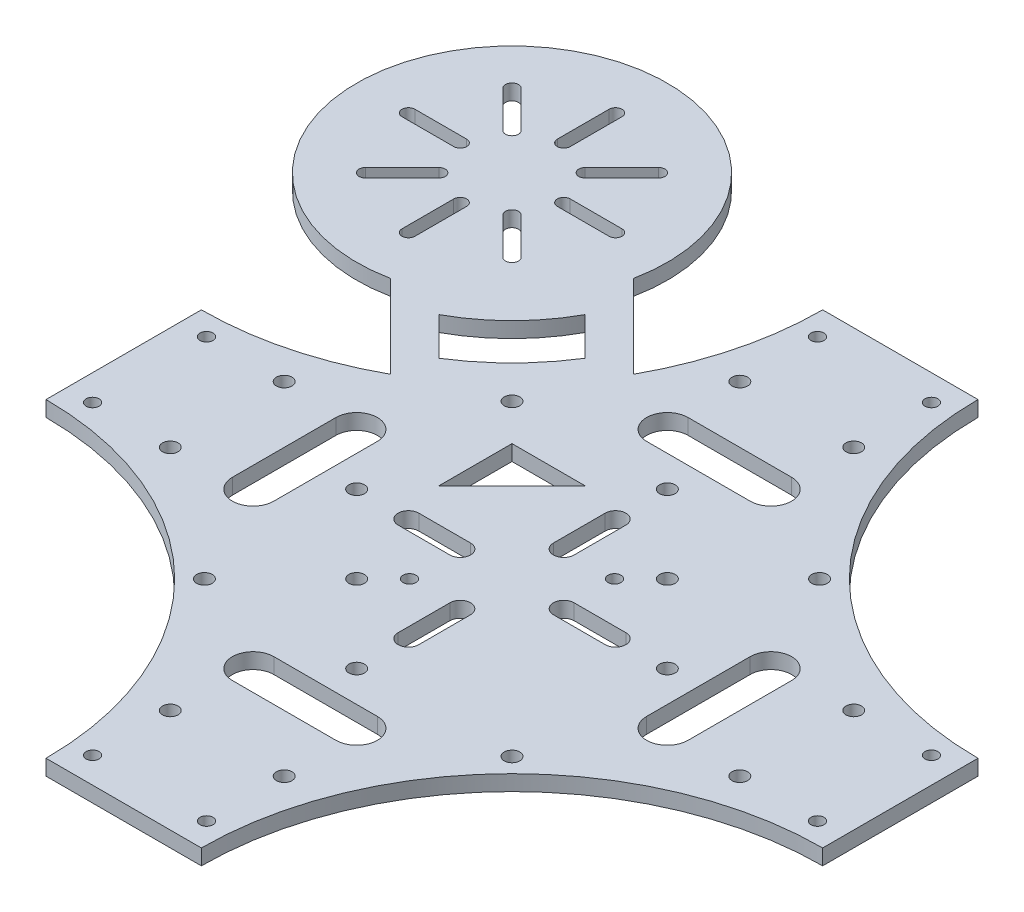
SolidWorks part; units mm, degrees
ref_plane "前视基准面" through (0, 0, 0) normal (0, 0, 1) x (1, 0, 0)
ref_plane "上视基准面" through (0, 0, 0) normal (0, 1, 0) x (1, 0, 0)
ref_plane "右视基准面" through (0, 0, 0) normal (1, 0, 0) x (0, 0, -1)
sketch "草图1" plane through (0, 0, 0) normal (0, 1, 0) x (1, 0, 0)
  line L0 (0, 0) -> (0, 75)
  line L1 (0, 0) -> (75, 0)
  line L2 (0, 0) -> (0, -75)
  line L3 (0, 0) -> (-75, 0)
  line L4 (0, 75) -> (15, 75)
  line L5 (0, 75) -> (-15, 75)
  line L6 (75, 0) -> (75, 15)
  line L7 (75, 0) -> (75, -15)
  line L8 (0, -75) -> (15, -75)
  line L9 (0, -75) -> (-15, -75)
  line L10 (-75, 0) -> (-75, -15)
  line L11 (-75, 0) -> (-75, 15)
  line L12 (75, 0) -> (70, 0)
  arc A0 (-75, 15) -> (-15, 75) centre (-75, 75) ccw
  arc A1 (15, 75) -> (75, 15) centre (75, 75) ccw
  arc A2 (75, -15) -> (15, -75) centre (75, -75) ccw
  arc A3 (-15, -75) -> (-75, -15) centre (-75, -75) ccw
  circle A4 centre (-11, 70) radius 1.25
  circle A5 centre (11, 70) radius 1.25
  circle A6 centre (70, -11) radius 1.25
  circle A7 centre (70, 11) radius 1.25
  circle A8 centre (-11, -70) radius 1.25
  circle A9 centre (11, -70) radius 1.25
  circle A10 centre (-70, 11) radius 1.25
  circle A11 centre (-70, -11) radius 1.25
  point P9 (0, 0)
  point P21 (0, 0)
  point P32 (0, 0)
  point P35 (0, 0)
  point P44 (0, 0)
  dimension "D1" = 4
extrude "凸台-拉伸1" add sketch "草图1" along normal blind 3 contours A2 L7 L1 L2 L8 A9 A6 | A3 L9 L2 L3 L10 A11 A8 | A0 L11 L3 L0 L5 A4 A10 | A1 L4 L0 L1 L6 A7 A5
sketch "草图2" plane through (0, 0, 0) normal (0, -1, 0) x (1, 0, 0)
  line L0 (0, 0) -> (-32.5736, -32.5736)
  line L1 (0, 0) -> (32.5736, -32.5736)
  line L2 (-31.4663, 0.3536) -> (-0.3536, 31.4663)
  line L3 (31.4663, -0.3536) -> (-0.3536, 31.4663)
  line L4 (0.3536, -31.4663) -> (31.4663, -0.3536)
  line L5 (0.3536, -31.4663) -> (-31.4663, 0.3536)
  arc A0 (-15, -75) -> (-75, -15) centre (-75, -75) ccw construction
  circle A2 centre (0.3536, -31.4663) radius 1.5
  circle A3 centre (31.4663, -0.3536) radius 1.5
  circle A4 centre (-0.3536, 31.4663) radius 1.5
  circle A5 centre (-31.4663, 0.3536) radius 1.5
  point P12 (-15.5563, -15.5563)
  point P16 (-15.9099, 15.9099)
  point P17 (15.9099, -15.9099)
extrude "切除-拉伸1" cut sketch "草图2" against normal blind 3 contours A3 | A2 | A5 | A4
sketch "草图3" plane through (0, 3, 0) normal (0, 1, 0) x (1, 0, 0)
  line L0 (0.3536, 31.4663) -> (-31.4663, -0.3536)
  line L1 (-15.5563, 15.5563) -> (-22.6274, 22.6274)
  line L2 (-15.5563, 15.5563) -> (-12.0208, 19.0919)
  line L3 (-15.5563, 15.5563) -> (-19.0919, 12.0208)
  line L4 (-19.0919, 12.0208) -> (-22.6274, 22.6274)
  line L5 (-12.0208, 19.0919) -> (-22.6274, 22.6274)
extrude "切除-拉伸2" cut sketch "草图3" against normal blind 3 contours L0 L5 L1 | L4 L0 L1
sketch "草图4" plane through (0, 3, 0) normal (0, 1, 0) x (1, 0, 0)
  line L0 (31.4663, 0.3536) -> (-0.3536, -31.4663)
  line L1 (0, 0) -> (21.2132, -21.2132)
  line L2 (28.2843, -14.1421) -> (14.1421, -28.2843)
  line L3 (14.1421, -28.2843) -> (28.2843, -14.1421) construction
  line L4 (8.4817, -22.6239) -> (22.6239, -8.4817)
  line L5 (19.8025, -33.9447) -> (33.9447, -19.8025)
  arc A0 (8.4817, -22.6239) -> (19.8025, -33.9447) centre (14.1421, -28.2843) ccw
  arc A1 (33.9447, -19.8025) -> (22.6239, -8.4817) centre (28.2843, -14.1421) ccw
  point P9 (21.2132, -21.2132)
extrude "切除-拉伸3" cut sketch "草图4" against normal blind 3
sketch "草图5" plane through (0, 3, 0) normal (0, 1, 0) x (1, 0, 0)
  line L0 (-12.0208, 19.0919) -> (-8.4853, 22.6274)
  line L1 (-8.4853, 22.6274) -> (-22.6274, 22.6274)
  line L2 (-19.0919, 12.0208) -> (-22.6274, 8.4853)
  line L3 (-22.6274, 8.4853) -> (-22.6274, 22.6274)
  line L4 (-12.0208, 19.0919) -> (-22.6274, 22.6274)
  line M28 (-19.0919, 12.0208) -> (-22.6274, 22.6274)
extrude "切除-拉伸4" cut sketch "草图5" against normal blind 10 contours L3 L2 M28 | L4 L0 L1
sketch "草图6" plane through (0, 3, 0) normal (0, 1, 0) x (1, 0, 0)
  line L0 (0, 0) -> (-28.2843, -28.2843)
  line L1 (-28.2843, -28.2843) -> (-35.3553, -21.2132)
  line L2 (0, 0) -> (-22.6274, 22.6274)
  circle A0 centre (-35.3553, -21.2132) radius 1.5
  circle A1 centre (-21.2132, -35.3553) radius 1.5
  circle A2 centre (35.3553, 21.2132) radius 1.5
  circle A3 centre (21.2132, 35.3553) radius 1.5
extrude "切除-拉伸5" cut sketch "草图6" against normal blind 10 contours A1 | A0 | A2 | A3
sketch "草图7" plane through (0, 3, 0) normal (0, 1, 0) x (1, 0, 0)
  circle A0 centre (-29.6985, 29.6985) radius 1.5
  circle A1 centre (29.6985, 29.6985) radius 1.5
  circle A2 centre (29.6985, -29.6985) radius 1.5
  circle A3 centre (-29.6985, -29.6985) radius 1.5
  point P11 (0, 0)
  dimension "D1" = 4
extrude "切除-拉伸8" cut sketch "草图7" against normal blind 10
sketch "草图8" plane through (0, 3, 0) normal (0, 1, 0) x (1, 0, 0)
  circle A0 centre (-11, 55) radius 1.5
  circle A1 centre (11, 55) radius 1.5
  circle A2 centre (55, 11) radius 1.5
  circle A3 centre (55, -11) radius 1.5
  circle A4 centre (11, -55) radius 1.5
  circle A5 centre (-11, -55) radius 1.5
  circle A6 centre (-55, -11) radius 1.5
  circle A7 centre (-55, 11) radius 1.5
  point P21 (0, 0)
  dimension "D1" = 4
extrude "切除-拉伸9" cut sketch "草图8" against normal blind 10
sketch "草图9" plane through (0, 3, 0) normal (0, 1, 0) x (1, 0, 0)
  circle A0 centre (0, 0) radius 15
extrude "切除-拉伸10" cut sketch "草图9" against normal blind 10
sketch "草图11" plane through (0, 3, 0) normal (0, 1, 0) x (1, 0, 0)
  circle A0 centre (-35.3553, -21.2132) radius 1.5
  circle A2 centre (35.3553, 21.2132) radius 1.5
  circle A3 centre (21.2132, 35.3553) radius 1.5
  circle A4 centre (0.3536, 31.4663) radius 1.5
  circle A5 centre (31.4663, 0.3536) radius 1.5
  circle A6 centre (-0.3536, -31.4663) radius 1.5
  circle A7 centre (-31.4663, -0.3536) radius 1.5
  circle A8 centre (-21.2132, -35.3553) radius 1.5
extrude "凸台-拉伸3" add sketch "草图11" against normal blind 3
sketch "草图12" plane through (0, 3, 0) normal (0, 1, 0) x (1, 0, 0)
  line L0 (0, 0) -> (-40, 0)
  line L1 (-40, 0) -> (-40, 10)
  line L2 (-40, 0) -> (-40, -10)
  line L3 (-40, -10) -> (-40, 10) construction
  line L4 (-44, -10) -> (-44, 10)
  line L5 (-36, -10) -> (-36, 10)
  line L6 (-10, 40) -> (10, 40) construction
  line L7 (-10, 44) -> (10, 44)
  line L8 (-10, 36) -> (10, 36)
  line L9 (40, 10) -> (40, -10) construction
  line L10 (44, 10) -> (44, -10)
  line L11 (36, 10) -> (36, -10)
  line L12 (10, -40) -> (-10, -40) construction
  line L13 (10, -44) -> (-10, -44)
  line L14 (10, -36) -> (-10, -36)
  arc A0 (-44, -10) -> (-36, -10) centre (-40, -10) ccw
  arc A1 (-36, 10) -> (-44, 10) centre (-40, 10) ccw
  arc A2 (-10, 44) -> (-10, 36) centre (-10, 40) ccw
  arc A3 (10, 36) -> (10, 44) centre (10, 40) ccw
  arc A4 (44, 10) -> (36, 10) centre (40, 10) ccw
  arc A5 (36, -10) -> (44, -10) centre (40, -10) ccw
  arc A6 (10, -44) -> (10, -36) centre (10, -40) ccw
  arc A7 (-10, -36) -> (-10, -44) centre (-10, -40) ccw
  point P3 (-40, 0)
  point P13 (0, 40)
  point P20 (40, 0)
  point P27 (0, -40)
  point P34 (0, 0)
  dimension "D1" = 4
extrude "切除-拉伸12" cut sketch "草图12" against normal blind 3
sketch "草图14" plane through (0, 3, 0) normal (0, 1, 0) x (1, 0, 0)
  line L0 (22.8277, -8.285) -> (8.285, -22.8277) construction
  line L1 (19.8025, -33.9447) -> (33.9447, -19.8025) construction
  line L2 (8.285, -22.8277) -> (22.8277, -8.285)
  line L3 (22.8277, -8.285) -> (19.8025, -33.9447)
  line L4 (19.8025, -33.9447) -> (33.9447, -19.8025)
  arc A0 (8.285, -22.8277) -> (19.8025, -33.9447) centre (14.1421, -28.2843) ccw
  arc A1 (8.285, -22.8277) -> (19.8025, -33.9447) centre (14.1421, -28.2843) ccw construction
  arc A2 (33.9447, -19.8025) -> (22.8277, -8.285) centre (28.2843, -14.1421) ccw construction
  arc A3 (22.8277, -8.285) -> (32.1857, -7.1522) centre (28.2843, -14.1421) ccw
  circle A4 centre (28.2843, -14.1421) radius 8.005
extrude "凸台-拉伸4" add sketch "草图14" against normal blind 3 contours A3 A4 L3 | L2 A3 L3 | A3 L2 A0 L3 | A3 L3 L4
sketch "草图15" plane through (0, 3, 0) normal (0, 1, 0) x (1, 0, 0)
  circle A0 centre (0, 0) radius 15
extrude "凸台-拉伸5" add sketch "草图15" against normal blind 3
sketch "草图17" plane through (0, 3, 0) normal (0, 1, 0) x (1, 0, 0)
  line L0 (0, 0) -> (0, -20)
  line L1 (0, -20) -> (0, -10) construction
  line L2 (-2, -20) -> (-2, -10)
  line L3 (2, -20) -> (2, -10)
  line L4 (-20, 0) -> (-10, 0) construction
  line L5 (-20, 2) -> (-10, 2)
  line L6 (-20, -2) -> (-10, -2)
  line L7 (0, 20) -> (0, 10) construction
  line L8 (2, 20) -> (2, 10)
  line L9 (-2, 20) -> (-2, 10)
  line L10 (20, 0) -> (10, 0) construction
  line L11 (20, -2) -> (10, -2)
  line L12 (20, 2) -> (10, 2)
  arc A0 (-2, -20) -> (2, -20) centre (0, -20) ccw
  arc A1 (2, -10) -> (-2, -10) centre (0, -10) ccw
  arc A2 (-20, 2) -> (-20, -2) centre (-20, 0) ccw
  arc A3 (-10, -2) -> (-10, 2) centre (-10, 0) ccw
  arc A4 (2, 20) -> (-2, 20) centre (0, 20) ccw
  arc A5 (-2, 10) -> (2, 10) centre (0, 10) ccw
  arc A6 (20, -2) -> (20, 2) centre (20, 0) ccw
  arc A7 (10, 2) -> (10, -2) centre (10, 0) ccw
  point P3 (0, -15)
  point P13 (-15, 0)
  point P20 (0, 15)
  point P27 (15, 0)
  point P33 (0, 0)
  dimension "D1" = 4
extrude "切除-拉伸13" cut sketch "草图17" against normal blind 3 contours L8 A5 L9 A4 | L12 A7 L11 A6 | L3 A1 L2 A0 | L5 A3 L6 A2
sketch "草图18" plane through (0, 3, 0) normal (0, 1, 0) x (1, 0, 0)
  line L0 (0, 0) -> (-32.5736, 32.5736)
  line L1 (-32.5736, 32.5736) -> (-46.7157, 46.7157)
  line L2 (-50.2513, 50.2513) -> (-61.9773, 38.5252)
  line L3 (-46.7157, 46.7157) -> (-50.2513, 50.2513)
  line L4 (-61.9773, 38.5252) -> (-38.5252, 61.9773)
  line L5 (-38.5252, 61.9773) -> (-22.5002, 45.9523)
  line L6 (-61.9773, 38.5252) -> (-45.9523, 22.5002)
  arc A0 (-75, 15) -> (-15, 75) centre (-75, 75) ccw construction
  circle A1 centre (-67.9289, 67.9289) radius 30
  circle A2 centre (-75, 75) radius 60
extrude "凸台-拉伸7" add sketch "草图18" against normal blind 3 contours L4 A1 L2 | L2 A1 L3 | L3 A1 L4 | L6 A2 L1 A1 | L1 A2 L5 A1
sketch "草图19" plane through (0, 3, 0) normal (0, 1, 0) x (1, 0, 0)
  line L0 (-61.9773, 38.5252) -> (-38.5252, 61.9773)
  line L1 (-50.2513, 50.2513) -> (-36.1091, 36.1091)
  line L2 (-36.1091, 36.1091) -> (-43.1802, 29.0381)
  line L3 (-36.1091, 36.1091) -> (-29.0381, 43.1802)
  line L4 (-29.0381, 43.1802) -> (-37.1408, 51.2829)
  line L5 (-37.1408, 51.2829) -> (-51.2829, 37.1408)
  line L6 (-51.2829, 37.1408) -> (-43.1802, 29.0381)
  circle A1 centre (-67.9289, 67.9289) radius 35
  circle A2 centre (-67.9289, 67.9289) radius 45
extrude "切除-拉伸14" cut sketch "草图19" against normal blind 3 contours L1 A2 L4 A1 | L6 A2 L1 A1
sketch "草图21" plane through (0, 3, 0) normal (0, 1, 0) x (1, 0, 0)
  line L0 (-61.9773, 38.5252) -> (-38.5252, 61.9773)
  line L1 (-67.9289, 67.9289) -> (-53.7868, 53.7868)
  line L2 (-82.0711, 82.0711) -> (-75, 75)
  line L3 (-67.9289, 67.9289) -> (-82.0711, 82.0711)
  line L4 (-53.7868, 53.7868) -> (-60.8579, 60.8579)
  line L5 (-82.0711, 82.0711) -> (-75, 75) construction
  line L6 (-81.1872, 82.955) -> (-74.1161, 75.8839)
  line L7 (-82.955, 81.1872) -> (-75.8839, 74.1161)
  line L8 (-60.8579, 60.8579) -> (-53.7868, 53.7868) construction
  line L9 (-59.974, 61.7417) -> (-52.9029, 54.6707)
  line L10 (-61.7417, 59.974) -> (-54.6707, 52.9029)
  arc A0 (-81.1872, 82.955) -> (-82.955, 81.1872) centre (-82.0711, 82.0711) ccw
  arc A1 (-75.8839, 74.1161) -> (-74.1161, 75.8839) centre (-75, 75) ccw
  arc A2 (-59.974, 61.7417) -> (-61.7417, 59.974) centre (-60.8579, 60.8579) ccw
  arc A3 (-54.6707, 52.9029) -> (-52.9029, 54.6707) centre (-53.7868, 53.7868) ccw
  point P2 (-78.5355, 78.5355)
  point P15 (-57.3223, 57.3223)
extrude "切除-拉伸15" cut sketch "草图21" against normal blind 3
pattern_circular "阵列(圆周)1" count 8 over 360 about axis through (-67.9289, 0, -67.9289) along (0, 1, 0) of "切除-拉伸15"
sketch "草图22" plane through (0, 3, 0) normal (0, 1, 0) x (1, 0, 0)
  line L0 (0, 0) -> (9.8995, 9.8995)
  line L1 (0, 0) -> (-9.8995, -9.8995)
  circle A0 centre (9.8995, 9.8995) radius 1.25
  circle A1 centre (-9.8995, -9.8995) radius 1.25
extrude "切除-拉伸17" cut sketch "草图22" against normal blind 3 contours A0 | A1
sketch "草图23" plane through (0, 3, 0) normal (0, 1, 0) x (1, 0, 0)
  circle A0 centre (0, 30) radius 1.5
  circle A1 centre (30, 0) radius 1.5
  circle A2 centre (0, -30) radius 1.5
  circle A3 centre (-30, 0) radius 1.5
  point P13 (0, 0)
  dimension "D1" = 4
extrude "切除-拉伸18" cut sketch "草图23" against normal blind 10
sketch "草图24" plane through (0, 3, 0) normal (0, 1, 0) x (1, 0, 0)
  circle A0 centre (-15, -15) radius 1.5
  circle A1 centre (15, 15) radius 1.5
extrude "切除-拉伸19" cut sketch "草图24" against normal blind 10
